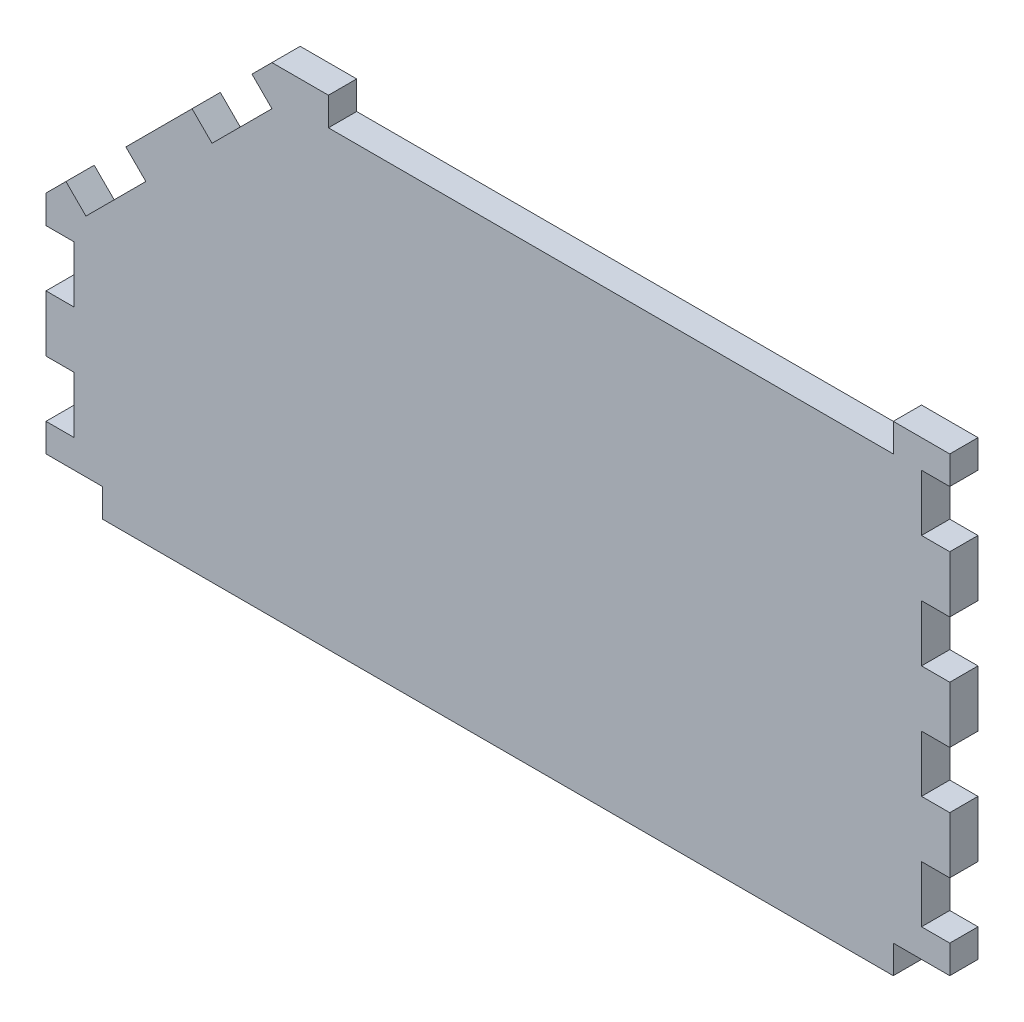
SolidWorks part; units mm, degrees
ref_plane "Plan de face" through (0, 0, 0) normal (0, 0, 1) x (1, 0, 0)
ref_plane "Plan de dessus" through (0, 0, 0) normal (0, 1, 0) x (1, 0, 0)
ref_plane "Plan de droite" through (0, 0, 0) normal (1, 0, 0) x (0, 0, -1)
sketch "Esquisse1" plane through (0, 0, 0) normal (0, 0, 1) x (1, 0, 0)
  line L0 (-80, 0) -> (-40, 40)
  line L4 (80, 40) -> (80, -40)
  line L6 (-70, -40) -> (-70, -45)
  line L7 (-70, -45) -> (70, -45)
  line L8 (70, -40) -> (70, -45)
  line L10 (-80, -25) -> (-75, -25)
  line L12 (-80, -35) -> (-75, -35)
  line L13 (-75, -25) -> (-75, -35)
  line L14 (-80, -5) -> (-75, -5)
  line L16 (-80, -15) -> (-75, -15)
  line L17 (-75, -5) -> (-75, -15)
  line L18 (-80, -40) -> (-80, -35)
  line L19 (-80, -5) -> (-80, 0)
  line L20 (-80, -25) -> (-80, -15)
  line L21 (-40, 40) -> (-30, 40)
  line L23 (-30, 40) -> (-30, 35)
  line L24 (-30, 35) -> (70, 35)
  line L25 (70, 40) -> (70, 35)
  line L26 (70, 40) -> (80, 40)
  line L27 (-80, -40) -> (-70, -40)
  line L28 (70, -40) -> (80, -40)
  dimension "D3" = 140
  dimension "D4" = 10
  dimension "D6" = 80
  dimension "D7" = 5
  dimension "D10" = 10
  dimension "D11" = 10
  dimension "D12" = 5
  dimension "D13" = 155
  dimension "D16" = 10
  dimension "D17" = 10
extrude "Boss.-Extru.1" add sketch "Esquisse1" along normal blind 5
sketch "Esquisse2" plane through (0, 0, 5) normal (0, 0, 1) x (1, 0, 0)
  line L0 (80, -40) -> (80, 40) construction
  line L1 (75, -25) -> (80, -25)
  line L2 (75, -25) -> (75, -35)
  line L3 (75, -35) -> (80, -35)
  line L4 (80, -25) -> (80, -35)
  line L5 (70, -40) -> (80, -40) construction
  line L6 (75, -5) -> (80, -5)
  line L7 (75, -5) -> (75, -15)
  line L8 (75, -15) -> (80, -15)
  line L9 (80, -5) -> (80, -15)
  line L10 (75, 15) -> (80, 15)
  line L11 (75, 15) -> (75, 5)
  line L12 (75, 5) -> (80, 5)
  line L13 (80, 15) -> (80, 5)
  line L14 (75, 35) -> (80, 35)
  line L15 (75, 35) -> (75, 25)
  line L16 (75, 25) -> (80, 25)
  line L17 (80, 35) -> (80, 25)
  dimension "D1" = 5
  dimension "D2" = 10
  dimension "D3" = 0
  dimension "D4" = 5
extrude "Enlèv. mat.-Extru.1" cut sketch "Esquisse2" against normal blind 10
sketch "Esquisse3" plane through (0, 0, 5) normal (0, 0, 1) x (1, 0, 0)
  line L0 (-43.5355, 36.4645) -> (-54.1421, 25.8579)
  line L1 (-43.5355, 36.4645) -> (-40, 32.9289)
  line L2 (-54.1421, 25.8579) -> (-50.6066, 22.3223)
  line L3 (-40, 32.9289) -> (-50.6066, 22.3223)
  line L4 (-40, 40) -> (-80, 0) construction
  line L5 (-65.8579, 14.1421) -> (-76.4645, 3.5355)
  line L6 (-65.8579, 14.1421) -> (-62.3223, 10.6066)
  line L7 (-76.4645, 3.5355) -> (-72.9289, 0)
  line L8 (-62.3223, 10.6066) -> (-72.9289, 0)
  point P6 (0, 0)
  dimension "D1" = 5
  dimension "D2" = 15
  dimension "D3" = 5
  dimension "D4" = 15
  dimension "D5" = 5
  dimension "D6" = 5
extrude "Enlèv. mat.-Extru.2" cut sketch "Esquisse3" against normal blind 10
